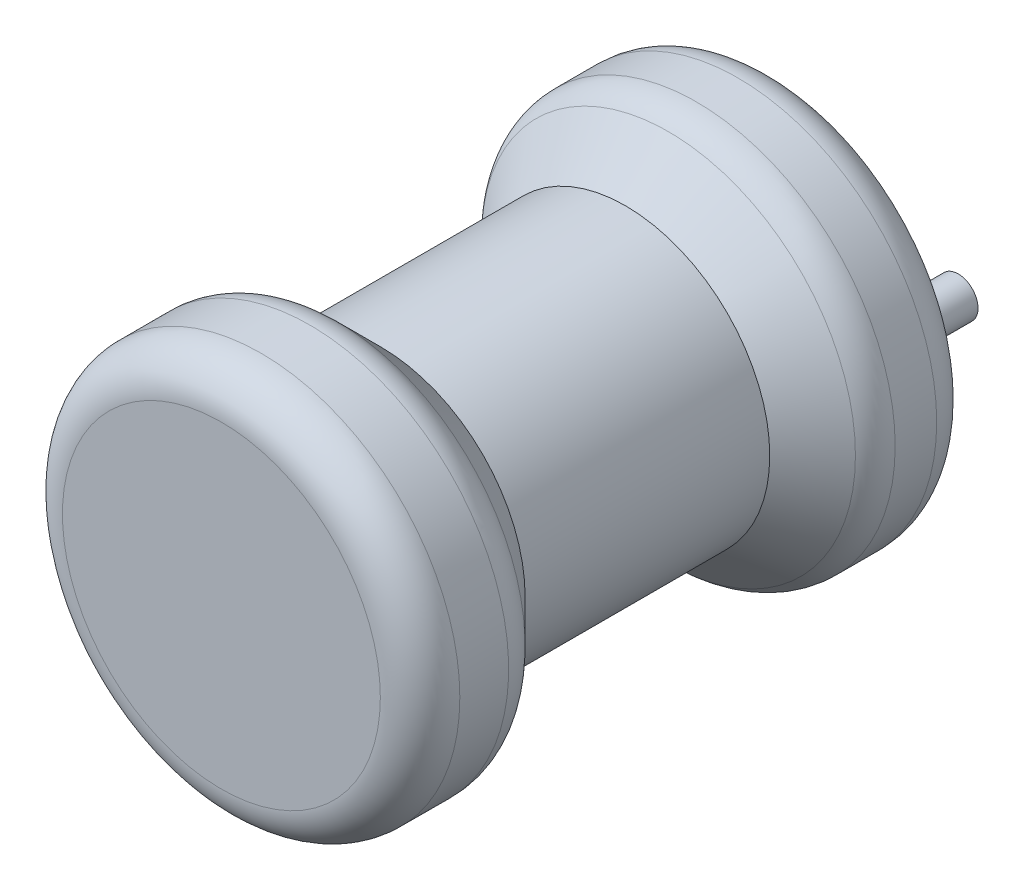
SolidWorks part; units mm, degrees
ref_plane "前视基准面" through (0, 0, 0) normal (0, 0, 1) x (1, 0, 0)
ref_plane "上视基准面" through (0, 0, 0) normal (0, 1, 0) x (1, 0, 0)
ref_plane "右视基准面" through (0, 0, 0) normal (1, 0, 0) x (0, 0, -1)
sketch "草图1" plane through (0, 0, 0) normal (0, 0, 1) x (1, 0, 0)
  circle A0 centre (0, 0) radius 5
  dimension "D1" = 10
extrude "凸台-拉伸1" add sketch "草图1" along normal blind 14
ref_axis "基准轴1" through (0, 0, -0.7) along (0, 0, 1)
sketch "草图3" plane through (0, 0, 0) normal (0, 1, 0) x (1, 0, 0)
  line L0 (-5.2731, -2.1863) -> (-3.6291, -3.8303)
  line L1 (-3.6291, -3.8303) -> (-3.6291, -9.9859)
  line L2 (-3.6291, -9.9859) -> (-5.2731, -11.63)
  line L3 (-5.2731, -11.63) -> (-5.2731, -2.1863)
revolve "切除-旋转1" cut sketch "草图3" angle 360 about axis through (0, 0, -0.7) along (0, 0, 1)
sketch "草图4" plane through (0, 0, 0) normal (0, 0, 1) x (1, 0, 0)
  line L0 (0, -1000) -> (0, 49000) construction
  circle A0 centre (-2.54, 0) radius 0.5
  circle A1 centre (2.54, 0) radius 0.5
  dimension "D1" = 1
  dimension "D2" = 5.08
extrude "凸台-拉伸2" add sketch "草图4" against normal blind 2
fillet "圆角2" radius 1 4 edges at (5, 0, 0) (-5, 0, 2.4594) (5, 0, 11.3569) (5, 0, 14)
